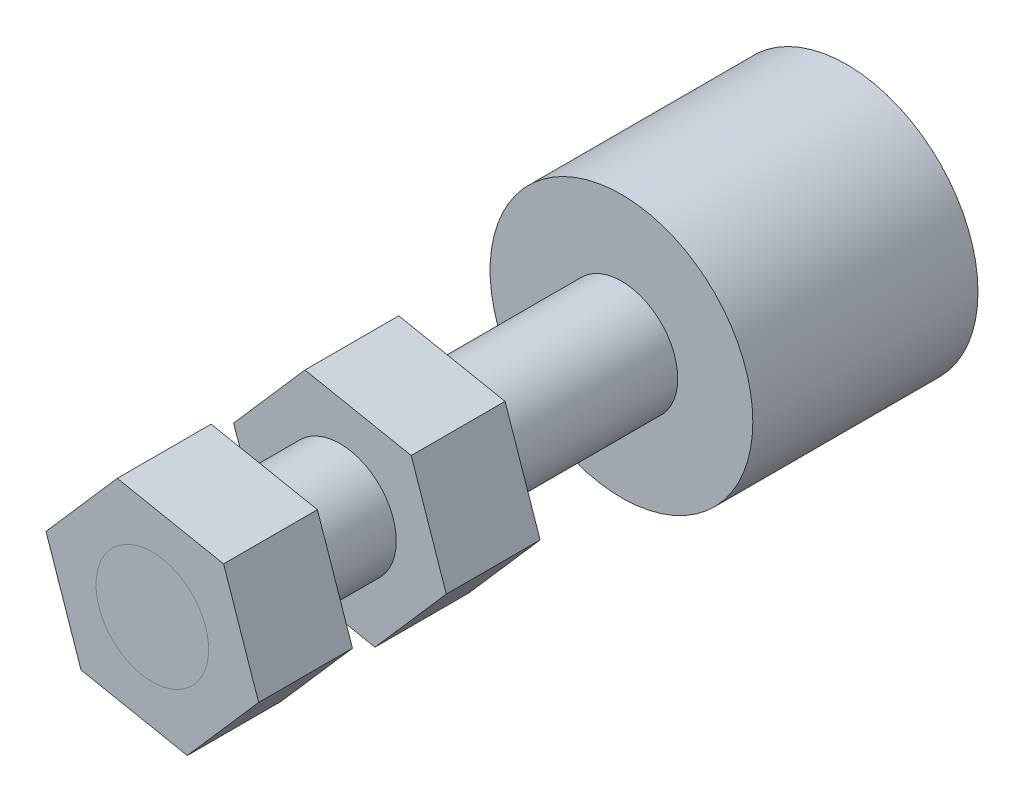
SolidWorks part; units mm, degrees
ref_plane "前视基准面" through (0, 0, 0) normal (0, 0, 1) x (1, 0, 0)
ref_plane "上视基准面" through (0, 0, 0) normal (0, 1, 0) x (1, 0, 0)
ref_plane "右视基准面" through (0, 0, 0) normal (1, 0, 0) x (0, 0, -1)
sketch "草图1" plane through (0, 0, 0) normal (0, 0, 1) x (1, 0, 0)
  circle A0 centre (0, 0) radius 7
  dimension "D1" = 14
extrude "凸台-拉伸1" add sketch "草图1" along normal blind 12
sketch "草图2" plane through (0, 0, 12) normal (0, 0, 1) x (1, 0, 0)
  circle A0 centre (0, 0) radius 3
  dimension "D1" = 6
extrude "凸台-拉伸2" add sketch "草图2" along normal blind 25
cosmetic thread "装饰螺纹线3" parameters "D1"=25, "D2"=5
sketch "草图3" plane through (0, 0, 37) normal (0, 0, 1) x (1, 0, 0)
  line L1 (3.7982, 4.3482) -> (-1.8665, 5.4635)
  line L2 (-1.8665, 5.4635) -> (-5.6648, 1.1153)
  line L3 (-5.6648, 1.1153) -> (-3.7982, -4.3482)
  line L4 (-3.7982, -4.3482) -> (1.8665, -5.4635)
  line L5 (1.8665, -5.4635) -> (5.6648, -1.1153)
  line L6 (5.6648, -1.1153) -> (3.7982, 4.3482)
  circle A0 centre (0, 0) radius 3
  circle A1 centre (0, 0) radius 5 construction
  dimension "D1" = 6
  dimension "D2" = 10
extrude "凸台-拉伸3" add sketch "草图3" against normal blind 5 separate body
cosmetic thread "装饰螺纹线1" parameters "D1"=5, "D2"=7
pattern_linear "阵列(线性)1" count 2 spacing 10 along (0, 0, -1) of bodies 108
cosmetic thread "装饰螺纹线2" parameters "D1"=5, "D2"=7
